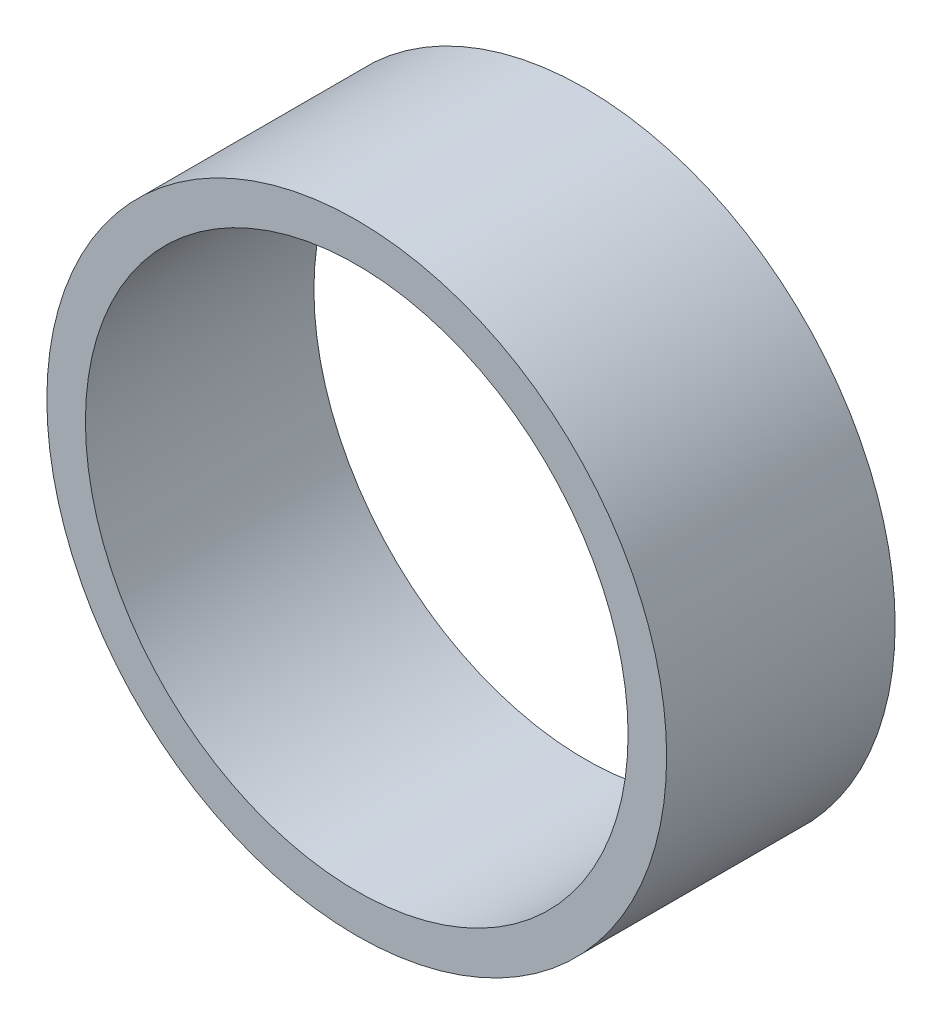
SolidWorks part; units mm, degrees
material "Custom Plastic"
ref_plane "X-Y Datum" through (0, 0, 0) normal (0, 0, 1) x (1, 0, 0)
ref_plane "X-Z Datum" through (0, 0, 0) normal (0, 1, 0) x (1, 0, 0)
ref_plane "Y-Z Datum" through (0, 0, 0) normal (1, 0, 0) x (0, 0, -1)
sketch "Sketch2" plane through (0, 0, 0) normal (0, 0, 1) x (1, 0, 0)
  circle A0 centre (0, 0) radius 4.75
  circle A1 centre (0, 0) radius 5.425
  dimension "D1" = 9.5
  dimension "D2" = 10.85
extrude "Boss-Extrude1" add sketch "Sketch2" along normal blind 4
